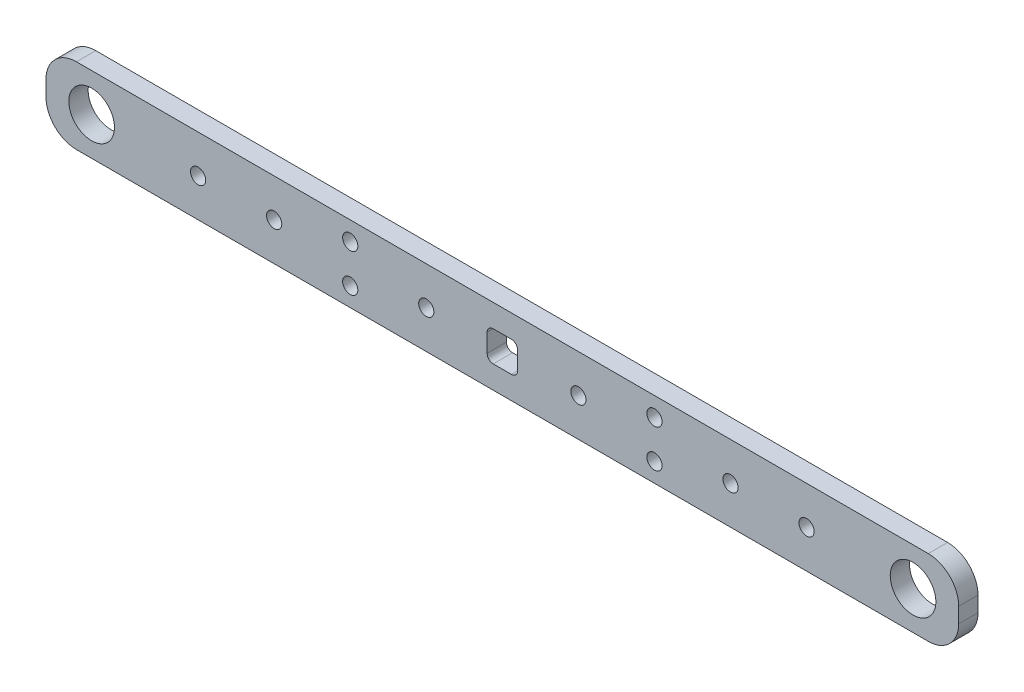
SolidWorks part; units mm, degrees
ref_plane "Front Plane" through (0, 0, 0) normal (0, 0, 1) x (1, 0, 0)
ref_plane "Top Plane" through (0, 0, 0) normal (0, 1, 0) x (1, 0, 0)
ref_plane "Right Plane" through (0, 0, 0) normal (1, 0, 0) x (0, 0, -1)
sketch "Sketch1" plane through (0, 0, 0) normal (0, 0, 1) x (1, 0, 0)
  line L0 (-150, 0) -> (150, 0) construction
  line L1 (-150, 12.5) -> (150, 12.5)
  line L2 (-150, 12.5) -> (-150, -12.5)
  line L3 (-150, -12.5) -> (150, -12.5)
  line L4 (150, 12.5) -> (150, -12.5)
  line L5 (-150, 12.5) -> (150, -12.5) construction
  line L6 (-150, -12.5) -> (150, 12.5) construction
  line L7 (0, 12.5) -> (0, -12.5) construction
  circle A0 centre (-135, 0) radius 7.5
  circle A1 centre (135, 0) radius 7.5
  point P0 (0, 0)
  dimension "D4" = 15
  dimension "D1" = 300
  dimension "D2" = 25
  dimension "D3" = 135
extrude "Boss-Extrude1" add sketch "Sketch1" along normal mid plane 6.35
fillet "Fillet1" radius 10 4 edges at (150, -12.5, 0) (-150, -12.5, 0) (-150, 12.5, 0) (150, 12.5, 0)
sketch "Sketch2" plane through (0, 0, 3.175) normal (0, 0, 1) x (1, 0, 0)
  line L0 (-150, 0) -> (150, 0) construction
  line L1 (-150, 2.5) -> (-150, -2.5) construction
  line L2 (150, -2.5) -> (150, 2.5) construction
  line L3 (150, 0) -> (0, 12.5) construction
  line L4 (140, 12.5) -> (-140, 12.5) construction
  line L5 (0, 12.5) -> (0, 0) construction
  line L7 (-5, 5) -> (5, 5)
  line L8 (-5, 5) -> (-5, -5)
  line L9 (-5, -5) -> (5, -5)
  line L10 (5, 5) -> (5, -5)
  line L11 (-5, 5) -> (5, -5) construction
  line L12 (-5, -5) -> (5, 5) construction
  circle A0 centre (-25, 0) radius 2.5
  circle A1 centre (-75, 0) radius 2.5
  circle A2 centre (25, 0) radius 2.5
  circle A3 centre (75, 0) radius 2.5
  dimension "D3" = 5
  dimension "D1" = 50
  dimension "D2" = 25
  dimension "D4" = 10
extrude "Cut-Extrude1" cut sketch "Sketch2" against normal through all both and the other way through all
fillet "Fillet2" radius 2 4 edges at (-5, -5, 0) (5, 5, 0) (5, -5, 0) (-5, 5, 0)
sketch "Sketch3" plane through (0, 0, 3.175) normal (0, 0, 1) x (1, 0, 0)
  line L0 (0, 0) -> (-50, 0) construction
  line L1 (-50, 0) -> (-50, 12.5) construction
  line L2 (140, 12.5) -> (-140, 12.5) construction
  line L3 (0, 0) -> (0, 12.5) construction
  line L4 (-150, 0) -> (-50, 0) construction
  line L5 (-150, 2.5) -> (-150, -2.5) construction
  circle A0 centre (-50, 6.25) radius 2.5
  circle A1 centre (-50, -6.25) radius 2.5
  circle A2 centre (50, -6.25) radius 2.5
  circle A3 centre (50, 6.25) radius 2.5
  circle A4 centre (-100, 0) radius 2.5
  circle A5 centre (100, 0) radius 2.5
  dimension "D2" = 5
  dimension "D3" = 5
  dimension "D1" = 50
extrude "Cut-Extrude2" cut sketch "Sketch3" against normal through all both and the other way through all
